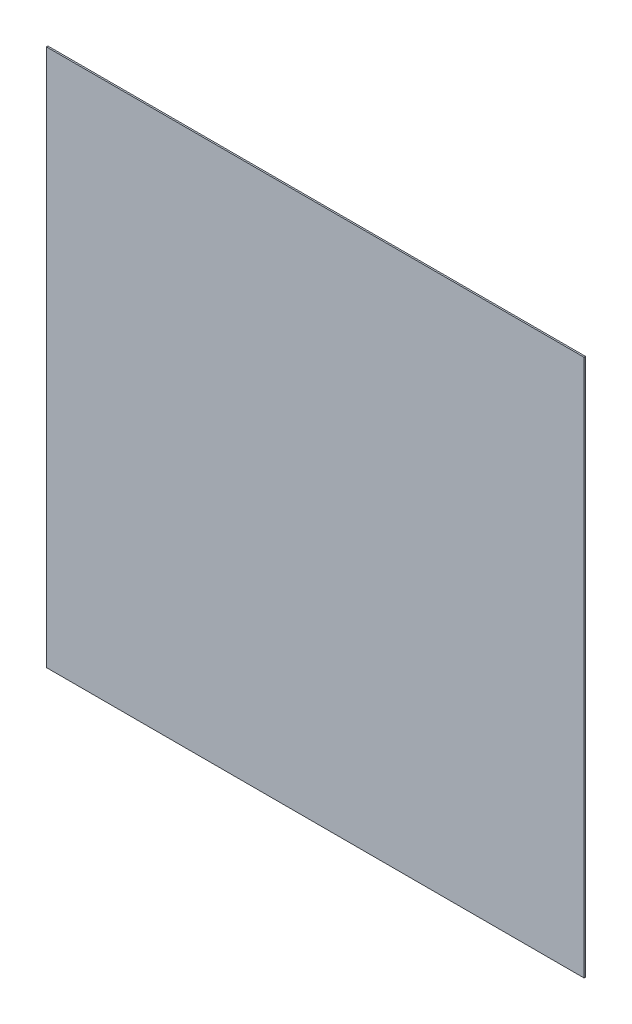
SolidWorks part; units mm, degrees
ref_plane "Front Plane" through (0, 0, 0) normal (0, 0, 1) x (1, 0, 0)
ref_plane "Top Plane" through (0, 0, 0) normal (0, 1, 0) x (1, 0, 0)
ref_plane "Right Plane" through (0, 0, 0) normal (1, 0, 0) x (0, 0, -1)
sketch "Sketch1" plane through (0, 0, 0) normal (0, 0, 1) x (1, 0, 0)
  line L0 (-450, 900) -> (-450, -900) construction
  line L9 (-900, 900) -> (900, 900)
  line L10 (-900, 900) -> (-900, -900)
  line L11 (-900, -900) -> (900, -900)
  line L12 (900, 900) -> (900, -900)
  line L13 (450, 900) -> (450, -900) construction
  line L15 (-450, 900) -> (450, 900)
  line L17 (-450, -900) -> (450, -900)
  point P0 (0, 0)
  point P5 (0, 0)
  dimension "D1" = 1800
  dimension "D2" = 450
  dimension "D4" = 1800
extrude "Boss-Extrude1" add sketch "Sketch1" along normal blind 5 contours L12 L9 L10 L11
